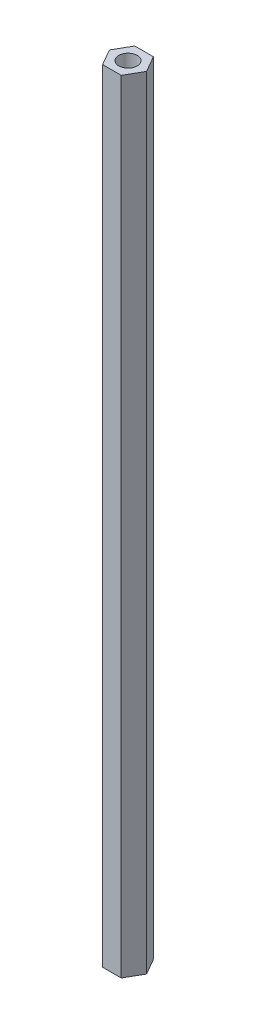
SolidWorks part; units mm, degrees
ref_plane "Front Plane" through (0, 0, 0) normal (0, 0, 1) x (1, 0, 0)
ref_plane "Top Plane" through (0, 0, 0) normal (0, 1, 0) x (1, 0, 0)
ref_plane "Right Plane" through (0, 0, 0) normal (1, 0, 0) x (0, 0, -1)
sketch "Sketch1" plane through (0, 0, 0) normal (0, 1, 0) x (1, 0, 0)
  line L1 (4.0415, 0) -> (2.0207, 3.5)
  line L2 (2.0207, 3.5) -> (-2.0207, 3.5)
  line L3 (-2.0207, 3.5) -> (-4.0415, 0)
  line L4 (-4.0415, 0) -> (-2.0207, -3.5)
  line L5 (-2.0207, -3.5) -> (2.0207, -3.5)
  line L6 (2.0207, -3.5) -> (4.0415, 0)
  circle A0 centre (0, 0) radius 3.5 construction
  circle A1 centre (0, 0) radius 2
  dimension "D1" = 4
  dimension "D2" = 7
extrude "Boss-Extrude1" add sketch "Sketch1" along normal blind 170
